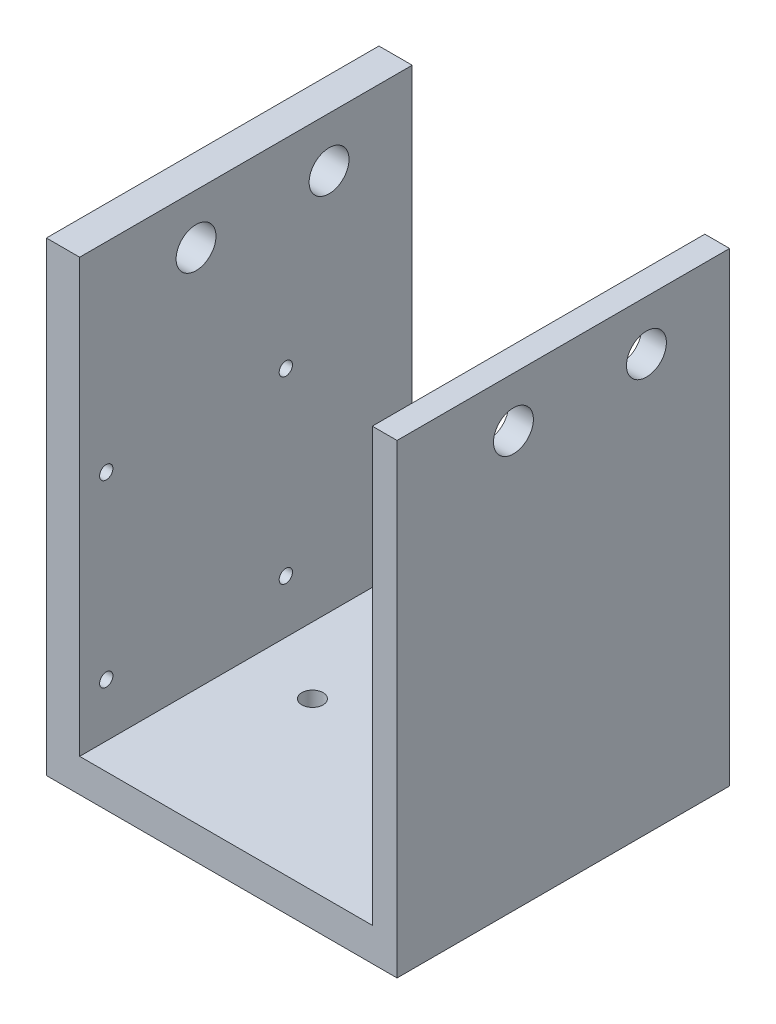
SolidWorks part; units mm, degrees
ref_plane "正面" through (0, 0, 0) normal (0, 0, 1) x (1, 0, 0)
ref_plane "平面" through (0, 0, 0) normal (0, 1, 0) x (1, 0, 0)
ref_plane "右側面" through (0, 0, 0) normal (1, 0, 0) x (0, 0, -1)
sketch "ｽｹｯﾁ1" plane through (0, 0, 0) normal (0, 0, 1) x (1, 0, 0)
  line L0 (-53.7139, 70) -> (-53.7139, 0)
  line L1 (27.5, 0) -> (-27.5, 0) construction
  line L2 (-53.7139, 0) -> (-4.7139, 0)
  line L3 (-4.7139, 0) -> (-4.7139, 5)
  line L4 (-4.7139, 5) -> (-48.7139, 5)
  line L7 (-53.7139, 70) -> (-48.7139, 70)
  line L8 (-48.7139, 70) -> (-48.7139, 5)
  dimension "D1" = 65
  dimension "D2" = 44
  dimension "D3" = 5
  dimension "D4" = 5
extrude "ﾎﾞｽ - 押し出し1" add sketch "ｽｹｯﾁ1" along normal blind 50
sketch "ｽｹｯﾁ2" plane through (-48.7139, 0, 0) normal (1, 0, 0) x (0, 0, -1)
  line L0 (-46, 40) -> (-46, 13) construction
  line L1 (-46, 13) -> (-19, 13) construction
  line L2 (-19, 13) -> (-19, 40) construction
  line L3 (-19, 40) -> (-46, 40) construction
  line L4 (-50, 5) -> (-50, 70) construction
  line L7 (-50, 5) -> (0, 5) construction
  circle A0 centre (-46, 40) radius 1
  circle A1 centre (-19, 40) radius 1
  circle A2 centre (-19, 13) radius 1
  circle A3 centre (-46, 13) radius 1
  dimension "D5" = 2
  dimension "D6" = 2
  dimension "D7" = 2
  dimension "D8" = 2
  dimension "D1" = 27
  dimension "D2" = 27
  dimension "D3" = 4
  dimension "D4" = 8
extrude "ｶｯﾄ - 押し出し1" cut sketch "ｽｹｯﾁ2" against normal through all
sketch "ｽｹｯﾁ3" plane through (0, 5, 0) normal (0, 1, 0) x (1, 0, 0)
  line L0 (-4.7139, -25) -> (-48.7139, -25) construction
  line L1 (-4.7139, -50) -> (-4.7139, 0) construction
  line L2 (-48.7139, -50) -> (-48.7139, 0) construction
  circle A0 centre (-38.7139, -25) radius 1.6
  circle A1 centre (-23.7139, -25) radius 1.6
  dimension "D1" = 3.2
  dimension "D2" = 3.2
  dimension "D3" = 15
  dimension "D4" = 10
extrude "ｶｯﾄ - 押し出し2" cut sketch "ｽｹｯﾁ3" against normal through all
sketch "ｽｹｯﾁ4" plane through (-48.7139, 0, 0) normal (1, 0, 0) x (0, 0, -1)
  line L0 (-50, 5) -> (-50, 70) construction
  line L1 (-50, 5) -> (0, 5) construction
  circle A0 centre (-32.5, 62.5) radius 3
  circle A1 centre (-12.5, 62.5) radius 3
  dimension "D3" = 6
  dimension "D4" = 6
  dimension "D1" = 17.5
  dimension "D2" = 57.5
  dimension "D5" = 20
extrude "ｶｯﾄ - 押し出し3" cut sketch "ｽｹｯﾁ4" against normal through all both and the other way through all
sketch "ｽｹｯﾁ5" plane through (0, 0, 50) normal (0, 0, 1) x (1, 0, 0)
  line L0 (-4.7139, 5) -> (-4.7139, 70)
  line L1 (-4.7139, 70) -> (-0.9898, 70)
  line L2 (-0.9898, 70) -> (-0.9898, 0)
  line L3 (27.5, 0) -> (-27.5, 0) construction
  line L4 (-0.9898, 0) -> (-4.7139, 0)
  line L5 (-4.7139, 0) -> (-4.7139, 5) construction
  line L6 (-4.7139, 0) -> (-4.7139, 5)
extrude "ﾎﾞｽ - 押し出し2" add sketch "ｽｹｯﾁ5" against normal blind 50
sketch "ｽｹｯﾁ6" plane through (-4.7139, 0, 0) normal (-1, 0, 0) x (0, 0, 1)
  circle A0 centre (12.5, 62.5) radius 3
  circle A3 centre (32.5, 62.5) radius 3 construction
  circle A4 centre (32.5, 62.5) radius 3
  point P3 (0, 0)
extrude "ｶｯﾄ - 押し出し4" cut sketch "ｽｹｯﾁ6" against normal through all
equation "\"D3@ｽｹｯﾁ2\"=(35-27)/2"
equation "\"a\"=50"
equation "\"D1@ﾎﾞｽ - 押し出し1\"=\"a\""
equation "\"D1@ｽｹｯﾁ4\"=\"35\"/2"
